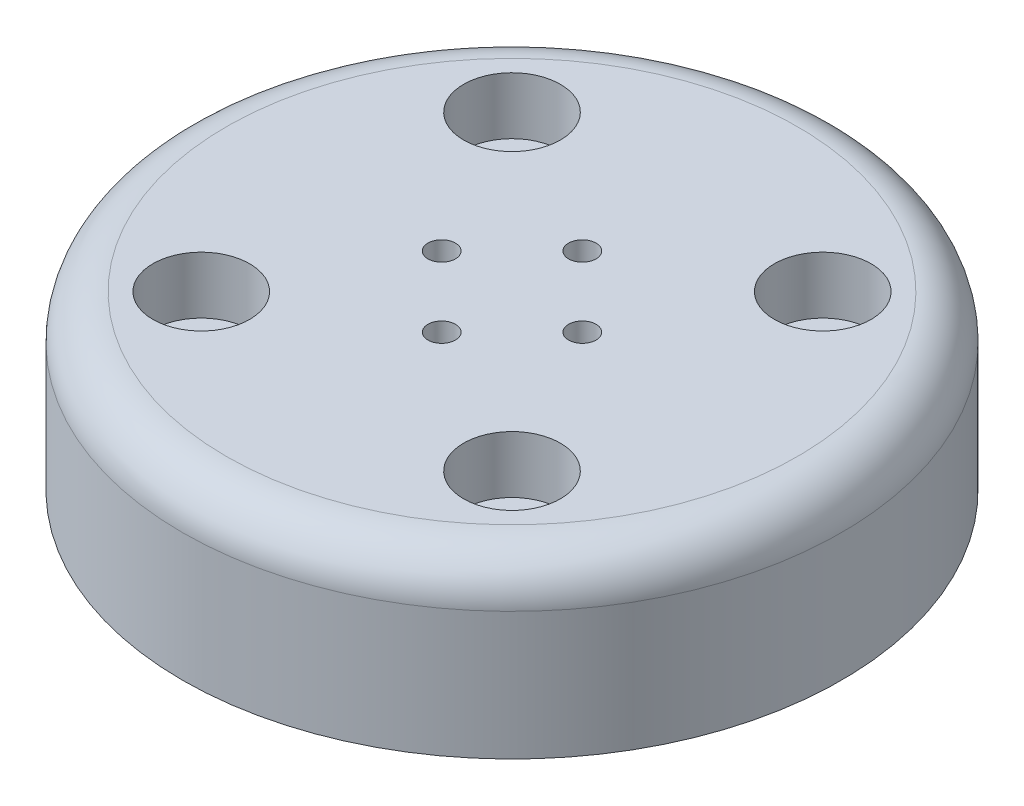
SolidWorks part; units mm, degrees
ref_plane "Front Plane" through (0, 0, 0) normal (0, 0, 1) x (1, 0, 0)
ref_plane "Top Plane" through (0, 0, 0) normal (0, 1, 0) x (1, 0, 0)
ref_plane "Right Plane" through (0, 0, 0) normal (1, 0, 0) x (0, 0, -1)
sketch "Sketch1" plane through (0, 0, 0) normal (0, 1, 0) x (1, 0, 0)
  circle A0 centre (0, 0) radius 37.5
  circle A1 centre (0, 0) radius 32
  dimension "D1" = 75
  dimension "D2" = 64
extrude "Boss-Extrude1" add sketch "Sketch1" along normal blind 6.7
sketch "Sketch2" plane through (0, 6.7, 0) normal (0, 1, 0) x (1, 0, 0)
  line L0 (-17.68, 17.68) -> (17.68, 17.68) construction
  line L1 (-17.68, -17.68) -> (-17.68, 17.68) construction
  line L2 (0, 8) -> (8, 0) construction
  line L3 (8, 0) -> (0, -8) construction
  line L4 (0, -8) -> (-8, 0) construction
  line L5 (-8, 0) -> (0, 8) construction
  line L6 (0, -8) -> (0, 8) construction
  circle A0 centre (0, 0) radius 37.5 construction
  circle A1 centre (0, 0) radius 37.5
  circle A2 centre (-17.68, 17.68) radius 3.4
  circle A3 centre (17.68, 17.68) radius 3.4
  circle A4 centre (17.68, -17.68) radius 3.4
  circle A5 centre (-17.68, -17.68) radius 3.4
  circle A6 centre (0, 8) radius 1.5625
  circle A7 centre (8, 0) radius 1.5625
  circle A8 centre (-8, 0) radius 1.5625
  circle A9 centre (0, -8) radius 1.5625
  point P11 (0, 17.68)
  point P12 (-17.68, 0)
  point P13 (0, 8)
  point P14 (-8, 0)
  point P15 (0, -8)
  point P16 (8, 0)
  point P19 (0, 0)
  dimension "D3" = 6.8
  dimension "D8" = 3.125
  dimension "D1" = 35.36
  dimension "D2" = 35.36
  dimension "D4" = 11.3137
  dimension "D5" = 11.3137
  dimension "D6" = 11.3137
  dimension "D7" = 11.3137
extrude "Boss-Extrude2" add sketch "Sketch2" along normal blind 12.85
sketch "Sketch3" plane through (0, 19.55, 0) normal (0, 1, 0) x (1, 0, 0)
  circle A0 centre (-17.68, -17.68) radius 3.4 construction
  circle A1 centre (17.68, -17.68) radius 3.4 construction
  circle A2 centre (17.68, 17.68) radius 3.4 construction
  circle A3 centre (-17.68, 17.68) radius 3.4 construction
  circle A4 centre (-17.68, -17.68) radius 3.4
  circle A5 centre (17.68, -17.68) radius 3.4
  circle A6 centre (17.68, 17.68) radius 3.4
  circle A7 centre (-17.68, 17.68) radius 3.4
  circle A8 centre (-17.68, 17.68) radius 5.5
  circle A9 centre (17.68, 17.68) radius 5.5
  circle A10 centre (17.68, -17.68) radius 5.5
  circle A11 centre (-17.68, -17.68) radius 5.5
  dimension "D1" = 11
extrude "Cut-Extrude1" cut sketch "Sketch3" against normal blind 6.5
sketch "Sketch4" plane through (0, 6.7, 0) normal (0, -1, 0) x (1, 0, 0)
  circle A0 centre (0, -8) radius 1.5625 construction
  circle A1 centre (8, 0) radius 1.5625 construction
  circle A2 centre (0, 8) radius 1.5625 construction
  circle A3 centre (-8, 0) radius 1.5625 construction
  circle A4 centre (0, -8) radius 1.5625
  circle A5 centre (8, 0) radius 1.5625
  circle A6 centre (0, 8) radius 1.5625
  circle A7 centre (-8, 0) radius 1.5625
  circle A8 centre (0, 8) radius 2.5
  circle A9 centre (8, 0) radius 2.5
  circle A10 centre (0, -8) radius 2.5
  circle A11 centre (-8, 0) radius 2.5
  dimension "D1" = 5
extrude "Cut-Extrude2" cut sketch "Sketch4" against normal blind 2.5
fillet "Fillet1" radius 5 1 edges at (0, 19.55, 37.5)
